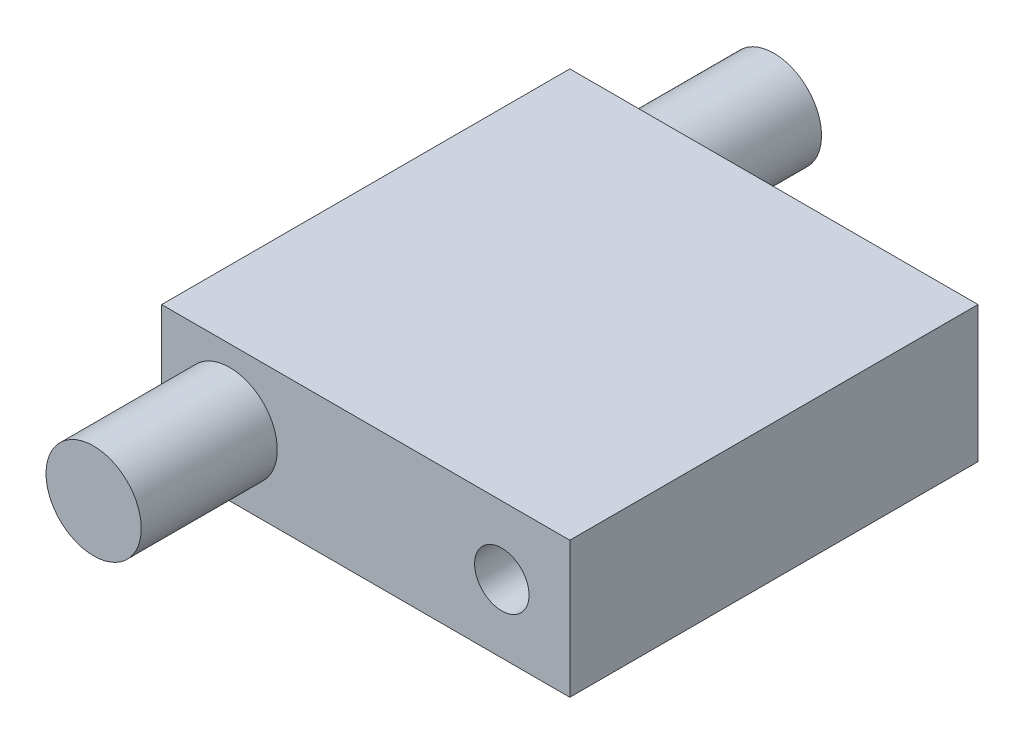
SolidWorks part; units mm, degrees
ref_plane "Front Plane" through (0, 0, 0) normal (0, 0, 1) x (1, 0, 0)
ref_plane "Top Plane" through (0, 0, 0) normal (0, 1, 0) x (1, 0, 0)
ref_plane "Right Plane" through (0, 0, 0) normal (1, 0, 0) x (0, 0, -1)
sketch "Sketch1" plane through (0, 0, 0) normal (0, 0, 1) x (1, 0, 0)
  line L1 (-300, -100) -> (300, -100)
  line L2 (-300, -100) -> (-300, 100)
  line L3 (-300, 100) -> (300, 100)
  line L4 (300, -100) -> (300, 100)
  line L5 (-300, -100) -> (300, 100) construction
  line L6 (-300, 100) -> (300, -100) construction
  point P0 (0, 0)
extrude "Boss-Extrude1" add sketch "Sketch1" along normal blind 600
sketch "Sketch2" plane through (0, 0, 600) normal (0, 0, 1) x (1, 0, 0)
  line L0 (0, 0) -> (200, 0) construction
  circle A0 centre (200, 0) radius 40
extrude "Cut-Extrude1" cut sketch "Sketch2" against normal blind 600 and the other way blind 40 contours A0
sketch "Sketch3" plane through (0, 0, 600) normal (0, 0, 1) x (1, 0, 0)
  line L0 (0, 0) -> (-200, 0) construction
  circle A0 centre (-200, 0) radius 70
extrude "Boss-Extrude2" add sketch "Sketch3" along normal blind 200
sketch "Sketch4" plane through (0, 0, 0) normal (0, 0, -1) x (-1, 0, 0)
  line L0 (0, 0) -> (200, 0) construction
  circle A0 centre (200, 0) radius 70
extrude "Boss-Extrude3" add sketch "Sketch4" along normal blind 200
